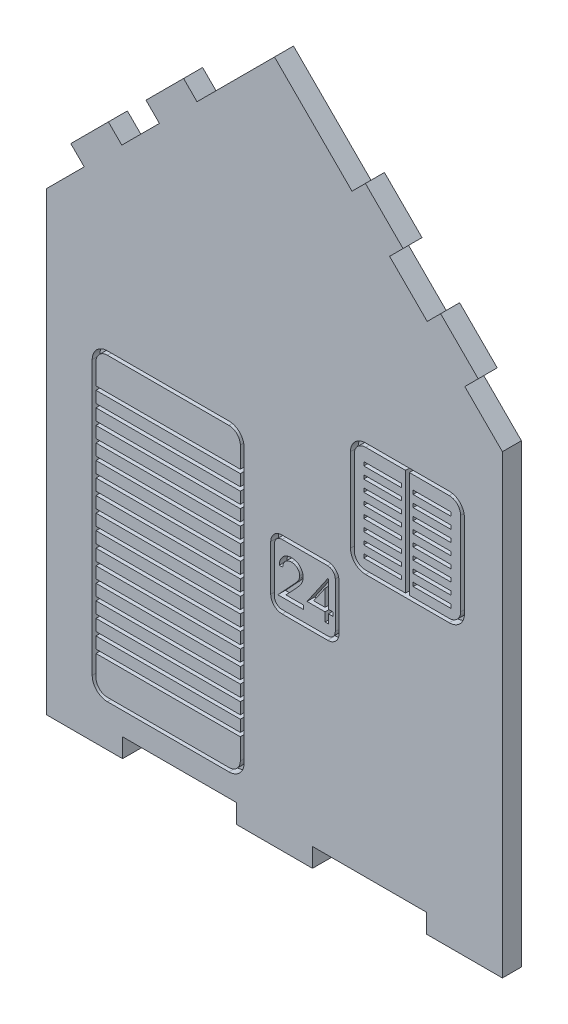
SolidWorks part; units mm, degrees
material "Beech"
ref_plane "Front" through (0, 0, 0) normal (0, 0, 1) x (1, 0, 0)
ref_plane "Top" through (0, 0, 0) normal (0, 1, 0) x (1, 0, 0)
ref_plane "Right" through (0, 0, 0) normal (1, 0, 0) x (0, 0, -1)
other "Back"
sketch "Sketch1" plane through (0, 0, 0) normal (0, 0, 1) x (1, 0, 0)
  line L0 (-30, -27.5) -> (30, -27.5) construction
  line L1 (-30, -30) -> (30, -30) construction
  line L2 (-30, -30) -> (-30, 30) construction
  line L3 (-30, 30) -> (30, 30) construction
  line L4 (30, -30) -> (30, 30) construction
  line L5 (-30, -30) -> (30, 30) construction
  line L6 (-30, 30) -> (30, -30) construction
  line L7 (-30, 30) -> (0, 60) construction
  line L8 (0, 60) -> (30, 30) construction
  line L9 (-30, 30) -> (-31.7678, 31.7678) construction
  line L10 (-31.7678, 31.7678) -> (-1.7678, 61.7678) construction
  line L11 (0, -7.61) -> (0, 9.5428) construction
  line L12 (0, 60) -> (-1.7678, 61.7678) construction
  line L13 (-30, 30) -> (-30, -30)
  line L14 (-30, -30) -> (-20, -30)
  line L15 (-20, -30) -> (-20, -27.5)
  line L16 (-20, -27.5) -> (-5, -27.5)
  line L17 (-5, -27.5) -> (-5, -30)
  line L18 (-5, -30) -> (5, -30)
  line L19 (-30, 30) -> (-25.0503, 34.9497)
  line L20 (-25.0503, 34.9497) -> (-26.818, 36.7175)
  line L21 (-26.818, 36.7175) -> (-21.8683, 41.6673)
  line L22 (-21.8683, 41.6673) -> (-20.1005, 39.8995)
  line L23 (-20.1005, 39.8995) -> (-15.1508, 44.8492)
  line L24 (-15.1508, 44.8492) -> (-16.9185, 46.617)
  line L25 (-16.9185, 46.617) -> (-11.9688, 51.5668)
  line L26 (-11.9688, 51.5668) -> (-10.201, 49.799)
  line L27 (-10.201, 49.799) -> (0, 60)
  line L28 (5, -27.5) -> (5, -30)
  line L29 (20, -27.5) -> (5, -27.5)
  line L30 (20, -30) -> (20, -27.5)
  line L31 (30, -30) -> (20, -30)
  line L32 (30, 30) -> (30, -30)
  line L33 (30, 30) -> (25.0503, 34.9497)
  line L34 (25.0503, 34.9497) -> (26.818, 36.7175)
  line L35 (26.818, 36.7175) -> (21.8683, 41.6673)
  line L36 (21.8683, 41.6673) -> (20.1005, 39.8995)
  line L37 (20.1005, 39.8995) -> (15.1508, 44.8492)
  line L38 (15.1508, 44.8492) -> (16.9185, 46.617)
  line L39 (16.9185, 46.617) -> (11.9688, 51.5668)
  line L40 (11.9688, 51.5668) -> (10.201, 49.799)
  line L41 (10.201, 49.799) -> (0, 60)
  point P0 (0, 0)
  point P30 (0, -30)
  dimension "D1" = 60
  dimension "D2" = 2.5
  dimension "D3" = 45
  dimension "D4" = 2.5
  dimension "D5" = 10
  dimension "D6" = 15
  dimension "D7" = 7
extrude "Boss-Extrude1" add sketch "Sketch1" along normal blind 2.5
sketch "Sketch2" plane through (0, 0, 2.5) normal (0, 0, 1) x (1, 0, 0)
  line L0 (-30, 30) -> (-30, -30) construction
  line L1 (-22, -24.5) -> (-6, -24.5)
  line L2 (-24, -22.5) -> (-24, 13.5)
  line L3 (-22, 15.5) -> (-6, 15.5)
  line L4 (-4, -22.5) -> (-4, 13.5)
  line L5 (-24, -24.5) -> (-4, 15.5) construction
  line L6 (-24, 15.5) -> (-4, -24.5) construction
  line L7 (12, 7) -> (23, 7)
  line L8 (10, 9) -> (10, 20)
  line L9 (12, 22) -> (23, 22)
  line L10 (25, 9) -> (25, 20)
  line L11 (10, 7) -> (25, 22) construction
  line L12 (10, 22) -> (25, 7) construction
  line L13 (-20, -27.5) -> (-5, -27.5) construction
  line L14 (30, -30) -> (30, 30) construction
  line L15 (-23.5, -22.5) -> (-23.5, 13.5)
  line L16 (-22, 15) -> (-6, 15)
  line L17 (-4.5, -22.5) -> (-4.5, 13.5)
  line L18 (-22, -24) -> (-6, -24)
  line L19 (10.5, 9) -> (10.5, 20)
  line L20 (12, 21.5) -> (23, 21.5)
  line L21 (24.5, 9) -> (24.5, 20)
  line L22 (12, 7.5) -> (23, 7.5)
  line L23 (17.5, 21.5) -> (17.5, 7.5) construction
  line L24 (17.25, 21.5) -> (17.25, 7.5)
  line L25 (17.75, 21.5) -> (17.75, 7.5)
  line L26 (18.25, 15.25) -> (23.25, 15.25)
  line L27 (23.25, 15.25) -> (23.25, 14.75)
  line L28 (23.25, 14.75) -> (18.25, 14.75)
  line L29 (18.25, 14.75) -> (18.25, 15.25)
  line L30 (11.75, 14.75) -> (16.75, 14.75)
  line L31 (16.75, 15.25) -> (11.75, 15.25)
  line L32 (16.75, 14.75) -> (16.75, 15.25)
  line L33 (11.75, 15.25) -> (11.75, 14.75)
  line L34 (11.75, 13.25) -> (16.75, 13.25)
  line L35 (16.75, 13.25) -> (16.75, 13.75)
  line L36 (16.75, 13.75) -> (11.75, 13.75)
  line L37 (11.75, 13.75) -> (11.75, 13.25)
  line L38 (18.25, 13.25) -> (18.25, 13.75)
  line L39 (18.25, 13.75) -> (23.25, 13.75)
  line L40 (23.25, 13.75) -> (23.25, 13.25)
  line L41 (23.25, 13.25) -> (18.25, 13.25)
  line L42 (11.75, 11.75) -> (16.75, 11.75)
  line L43 (16.75, 11.75) -> (16.75, 12.25)
  line L44 (16.75, 12.25) -> (11.75, 12.25)
  line L45 (11.75, 12.25) -> (11.75, 11.75)
  line L46 (18.25, 11.75) -> (18.25, 12.25)
  line L47 (18.25, 12.25) -> (23.25, 12.25)
  line L48 (23.25, 12.25) -> (23.25, 11.75)
  line L49 (23.25, 11.75) -> (18.25, 11.75)
  line L50 (11.75, 10.25) -> (16.75, 10.25)
  line L51 (16.75, 10.25) -> (16.75, 10.75)
  line L52 (16.75, 10.75) -> (11.75, 10.75)
  line L53 (11.75, 10.75) -> (11.75, 10.25)
  line L54 (18.25, 10.25) -> (18.25, 10.75)
  line L55 (18.25, 10.75) -> (23.25, 10.75)
  line L56 (23.25, 10.75) -> (23.25, 10.25)
  line L57 (23.25, 10.25) -> (18.25, 10.25)
  line L58 (11.75, 8.75) -> (16.75, 8.75)
  line L59 (16.75, 8.75) -> (16.75, 9.25)
  line L60 (16.75, 9.25) -> (11.75, 9.25)
  line L61 (11.75, 9.25) -> (11.75, 8.75)
  line L62 (18.25, 8.75) -> (18.25, 9.25)
  line L63 (18.25, 9.25) -> (23.25, 9.25)
  line L64 (23.25, 9.25) -> (23.25, 8.75)
  line L65 (23.25, 8.75) -> (18.25, 8.75)
  line L66 (-23.5, 10.75) -> (-4.5, 10.75)
  line L67 (-4.5, 10.25) -> (-23.5, 10.25)
  line L68 (-23.5, 8.75) -> (-4.5, 8.75)
  line L69 (-4.5, 8.25) -> (-23.5, 8.25)
  line L70 (-23.5, 6.75) -> (-4.5, 6.75)
  line L71 (-4.5, 6.25) -> (-23.5, 6.25)
  line L72 (-23.5, 4.75) -> (-4.5, 4.75)
  line L73 (-4.5, 4.25) -> (-23.5, 4.25)
  line L74 (-23.5, 2.75) -> (-4.5, 2.75)
  line L75 (-4.5, 2.25) -> (-23.5, 2.25)
  line L76 (-23.5, 0.75) -> (-4.5, 0.75)
  line L77 (-4.5, 0.25) -> (-23.5, 0.25)
  line L78 (-23.5, -1.25) -> (-4.5, -1.25)
  line L79 (-4.5, -1.75) -> (-23.5, -1.75)
  line L80 (-23.5, -3.25) -> (-4.5, -3.25)
  line L81 (-4.5, -3.75) -> (-23.5, -3.75)
  line L82 (-23.5, -5.25) -> (-4.5, -5.25)
  line L83 (-4.5, -5.75) -> (-23.5, -5.75)
  line L84 (-23.5, -7.25) -> (-4.5, -7.25)
  line L85 (-4.5, -7.75) -> (-23.5, -7.75)
  line L86 (-23.5, -9.25) -> (-4.5, -9.25)
  line L87 (-4.5, -9.75) -> (-23.5, -9.75)
  line L88 (-23.5, -11.25) -> (-4.5, -11.25)
  line L89 (-4.5, -11.75) -> (-23.5, -11.75)
  line L90 (-23.5, -13.25) -> (-4.5, -13.25)
  line L91 (-4.5, -13.75) -> (-23.5, -13.75)
  line L92 (-23.5, -15.25) -> (-4.5, -15.25)
  line L93 (-4.5, -15.75) -> (-23.5, -15.75)
  line L94 (-23.5, -17.25) -> (-4.5, -17.25)
  line L95 (-4.5, -17.75) -> (-23.5, -17.75)
  line L96 (-23.5, -19.25) -> (-4.5, -19.25)
  line L97 (-4.5, -19.75) -> (-23.5, -19.75)
  line L98 (18.25, 16.25) -> (18.25, 16.75)
  line L99 (1, -2.5) -> (7, -2.5)
  line L100 (0, -1.5) -> (0, 4.5)
  line L101 (1, 5.5) -> (7, 5.5)
  line L102 (8, -1.5) -> (8, 4.5)
  line L103 (0, -2.5) -> (8, 5.5) construction
  line L104 (0, 5.5) -> (8, -2.5) construction
  line L105 (18.25, 16.75) -> (23.25, 16.75)
  line L106 (23.25, 16.75) -> (23.25, 16.25)
  line L107 (23.25, 16.25) -> (18.25, 16.25)
  line L108 (11.75, 16.25) -> (16.75, 16.25)
  line L109 (16.75, 16.25) -> (16.75, 16.75)
  line L110 (16.75, 16.75) -> (11.75, 16.75)
  line L111 (11.75, 16.75) -> (11.75, 16.25)
  line L112 (18.25, 17.75) -> (18.25, 18.25)
  line L113 (18.25, 18.25) -> (23.25, 18.25)
  line L114 (23.25, 18.25) -> (23.25, 17.75)
  line L115 (23.25, 17.75) -> (18.25, 17.75)
  line L116 (11.75, 17.75) -> (16.75, 17.75)
  line L117 (16.75, 17.75) -> (16.75, 18.25)
  line L118 (16.75, 18.25) -> (11.75, 18.25)
  line L119 (11.75, 18.25) -> (11.75, 17.75)
  line L120 (18.25, 19.25) -> (18.25, 19.75)
  line L121 (18.25, 19.75) -> (23.25, 19.75)
  line L122 (23.25, 19.75) -> (23.25, 19.25)
  line L123 (23.25, 19.25) -> (18.25, 19.25)
  line L124 (11.75, 19.25) -> (16.75, 19.25)
  line L125 (16.75, 19.25) -> (16.75, 19.75)
  line L126 (16.75, 19.75) -> (11.75, 19.75)
  line L127 (11.75, 19.75) -> (11.75, 19.25)
  line L128 (1, -3) -> (7, -3)
  line L129 (8.5, -1.5) -> (8.5, 4.5)
  line L130 (1, 6) -> (7, 6)
  line L131 (-0.5, -1.5) -> (-0.5, 4.5)
  arc A0 (23, 7) -> (25, 9) centre (23, 9) ccw
  arc A1 (10, 20) -> (12, 22) centre (12, 20) cw
  arc A2 (12, 7) -> (10, 9) centre (12, 9) cw
  arc A3 (23, 22) -> (25, 20) centre (23, 20) cw
  arc A4 (-6, -24.5) -> (-4, -22.5) centre (-6, -22.5) ccw
  arc A5 (-24, 13.5) -> (-22, 15.5) centre (-22, 13.5) cw
  arc A6 (-22, -24.5) -> (-24, -22.5) centre (-22, -22.5) cw
  arc A7 (-6, 15.5) -> (-4, 13.5) centre (-6, 13.5) cw
  arc A8 (-23.5, 13.5) -> (-22, 15) centre (-22, 13.5) cw
  arc A9 (-6, 15) -> (-4.5, 13.5) centre (-6, 13.5) cw
  arc A10 (-6, -24) -> (-4.5, -22.5) centre (-6, -22.5) ccw
  arc A11 (-22, -24) -> (-23.5, -22.5) centre (-22, -22.5) cw
  arc A12 (10.5, 20) -> (12, 21.5) centre (12, 20) cw
  arc A13 (23, 21.5) -> (24.5, 20) centre (23, 20) cw
  arc A14 (23, 7.5) -> (24.5, 9) centre (23, 9) ccw
  arc A15 (12, 7.5) -> (10.5, 9) centre (12, 9) cw
  arc A16 (12, 7) -> (10, 9) centre (12, 9) cw construction
  arc A17 (0, 4.5) -> (1, 5.5) centre (1, 4.5) cw
  arc A18 (1, -2.5) -> (0, -1.5) centre (1, -1.5) cw
  arc A19 (7, -2.5) -> (8, -1.5) centre (7, -1.5) ccw
  arc A20 (7, 5.5) -> (8, 4.5) centre (7, 4.5) cw
  arc A21 (7, -3) -> (8.5, -1.5) centre (7, -1.5) ccw
  arc A22 (7, 6) -> (8.5, 4.5) centre (7, 4.5) cw
  arc A23 (-0.5, 4.5) -> (1, 6) centre (1, 4.5) cw
  arc A24 (1, -3) -> (-0.5, -1.5) centre (1, -1.5) cw
  point P0 (-14, -4.5)
  point P5 (17.5, 14.5)
  point P179 (4, 1.5)
  dimension "D8" = 2
  dimension "D27" = 1
  dimension "D1" = 15
  dimension "D2" = 40
  dimension "D3" = 20
  dimension "D4" = 6
  dimension "D5" = 3
  dimension "D6" = 5
  dimension "D7" = 8
  dimension "D12" = 0.5
  dimension "D13" = 0.5
  dimension "D14" = 5
  dimension "D16" = 1
  dimension "D17" = 1.25
  dimension "D18" = 0.5
  dimension "D19" = 4.25
  dimension "D21" = 1.5
  dimension "D22" = 8
  dimension "D23" = 4
  dimension "D24" = 10
  dimension "D25" = 4
  dimension "D26" = 1
  dimension "D9" = 0.5
  dimension "D10" = 0.25
  dimension "D11" = 0.25
  dimension "D28" = 0.5
  dimension "D15" = 5
  dimension "D20" = 16
extrude "Cut-Extrude1" cut sketch "Sketch2" against normal blind 1 contours A3 L9 A1 L8 A2 L7 A0 L10 L22 A15 L19 A12 L20 A13 L21 A14 | L31 L33 L30 L32 | L36 L37 L34 L35 | L44 L45 L42 L43 | L52 L53 L50 L51 | L60 L61 L58 L59 | L65 L64 L63 L62 | L57 L56 L55 L54 | L49 L48 L47 L46 | L41 L40 L39 L38 | L29 L28 L27 L26 | L25 L20 L24 L22 | A7 L3 A5 L2 A6 L1 A4 L4 L18 A11 L15 A8 L16 A9 L17 A10 | L67 L17 L66 L15 | L69 L17 L68 L15 | L71 L17 L70 L15 | L73 L17 L72 L15 | L75 L17 L74 L15 | L77 L17 L76 L15 | L79 L17 L78 L15 | L83 L17 L82 L15 | L85 L17 L84 L15 | L87 L17 L86 L15 | L81 L17 L80 L15 | L89 L17 L88 L15 | L91 L17 L90 L15 | L93 L17 L92 L15 | L95 L17 L94 L15 | L97 L17 L96 L15 | L110 L111 L108 L109 | L118 L119 L116 L117 | L126 L127 L124 L125 | L115 L114 L113 L112 | A24 L128 A21 L129 A22 L130 A23 L131 L101 A20 L102 A19 L99 A18 L100 A17 | L121 L122 L123 L120 | L105 L106 L107 L98
sketch "Sketch4" plane through (0, 0, 2.5) normal (0, 0, 1) x (1, 0, 0)
  text T0 "24" font "Century Gothic" height 5
extrude "Cut-Extrude2" cut sketch "Sketch4" against normal blind 1
sketch "Sketch5" [suppressed] plane through (0, 0, 0) normal (0, 0, -1) x (-1, 0, 0)
  line L0 (-27.5, -5) -> (-30, -5)
  line L1 (-27.5, -5) -> (-27.5, 5)
  line L2 (-27.5, 5) -> (-30, 5)
  line L3 (-30, -5) -> (-30, 5)
  line L4 (-27.5, -5) -> (-30, 5) construction
  line L5 (-27.5, 5) -> (-30, -5) construction
  line L6 (0, -0.4402) -> (0, 0.4402) construction
  line L7 (27.5, 5) -> (30, 5)
  line L8 (30, -5) -> (30, 5)
  line L9 (27.5, -5) -> (30, -5)
  line L10 (27.5, -5) -> (27.5, 5)
  line L11 (30, 30) -> (30, -30) construction
  line L13 (-20, -30) -> (-30, -30) construction
  point P4 (-28.75, 0)
  dimension "D1" = 10
  dimension "D2" = 2.5
  dimension "D3" = 25
extrude "Cut-Extrude3" [suppressed] cut sketch "Sketch5" against normal blind 2.5
